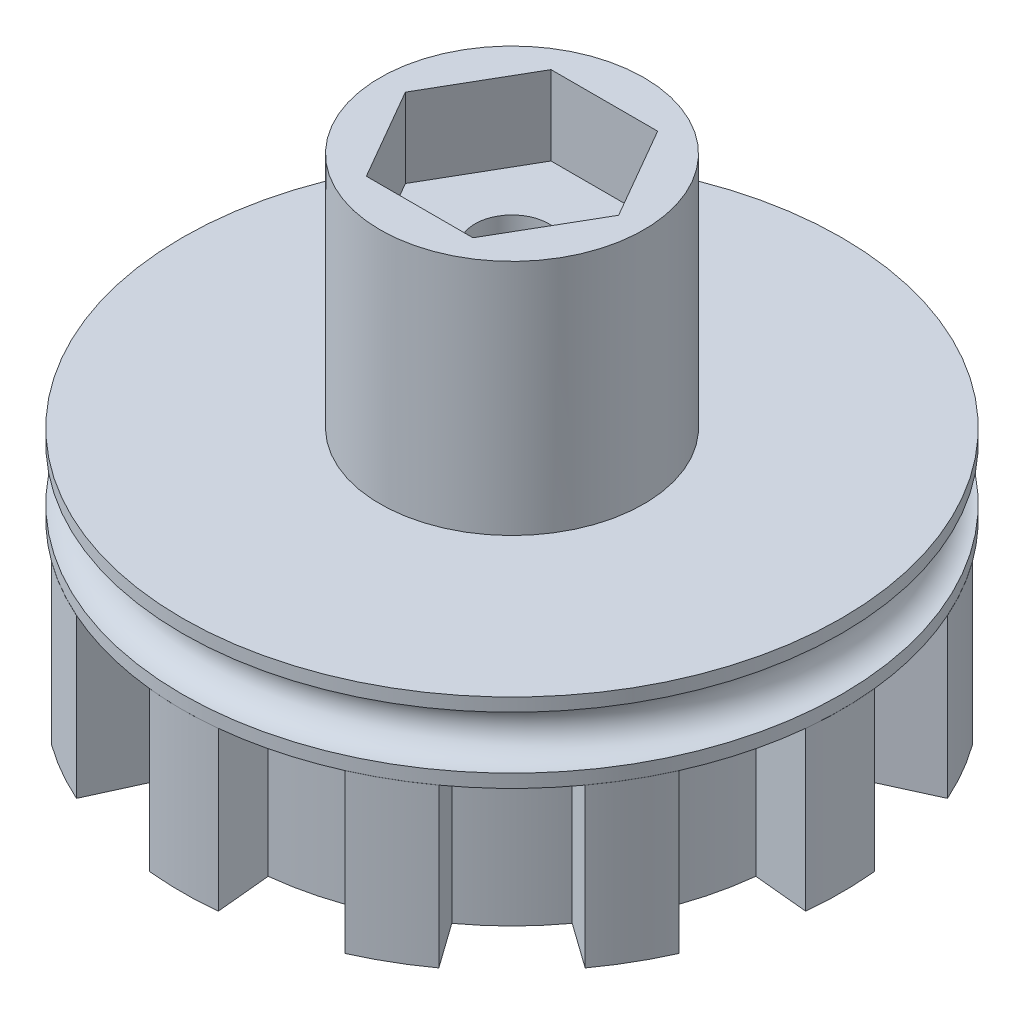
SolidWorks part; units mm, degrees
ref_plane "前视基准面" through (0, 0, 0) normal (0, 0, 1) x (1, 0, 0)
ref_plane "上视基准面" through (0, 0, 0) normal (0, 1, 0) x (1, 0, 0)
ref_plane "右视基准面" through (0, 0, 0) normal (1, 0, 0) x (0, 0, -1)
sketch "草图2" plane through (0, 0, 0) normal (0, 1, 0) x (1, 0, 0)
  line L0 (0, 13.0353) -> (0, -8.9877) construction
  line L1 (-1.1, 10.3417) -> (-1.3, 12.4322)
  line L2 (1.1, 10.3417) -> (1.3, 12.4322)
  line L3 (4.2182, 9.5061) -> (5.0903, 11.4166)
  line L4 (6.1235, 8.4061) -> (7.3419, 10.1166)
  line L5 (8.4061, 6.1235) -> (10.1166, 7.3419)
  line L6 (9.5061, 4.2182) -> (11.4166, 5.0903)
  line L7 (10.3417, 1.1) -> (12.4322, 1.3)
  line L8 (10.3417, -1.1) -> (12.4322, -1.3)
  line L9 (9.5061, -4.2182) -> (11.4166, -5.0903)
  line L10 (8.4061, -6.1235) -> (10.1166, -7.3419)
  line L11 (6.1235, -8.4061) -> (7.3419, -10.1166)
  line L12 (4.2182, -9.5061) -> (5.0903, -11.4166)
  line L13 (1.1, -10.3417) -> (1.3, -12.4322)
  line L14 (-1.1, -10.3417) -> (-1.3, -12.4322)
  line L15 (-4.2182, -9.5061) -> (-5.0903, -11.4166)
  line L16 (-6.1235, -8.4061) -> (-7.3419, -10.1166)
  line L17 (-8.4061, -6.1235) -> (-10.1166, -7.3419)
  line L18 (-9.5061, -4.2182) -> (-11.4166, -5.0903)
  line L19 (-10.3417, -1.1) -> (-12.4322, -1.3)
  line L20 (-10.3417, 1.1) -> (-12.4322, 1.3)
  line L21 (-9.5061, 4.2182) -> (-11.4166, 5.0903)
  line L22 (-8.4061, 6.1235) -> (-10.1166, 7.3419)
  line L23 (-6.1235, 8.4061) -> (-7.3419, 10.1166)
  line L24 (-4.2182, 9.5061) -> (-5.0903, 11.4166)
  arc A0 (-1.1, 10.3417) -> (-4.2182, 9.5061) centre (0, 0) ccw
  arc A1 (1.3, 12.4322) -> (-1.3, 12.4322) centre (0, 0) ccw
  arc A2 (7.3419, 10.1166) -> (5.0903, 11.4166) centre (0, 0) ccw
  arc A3 (11.4166, 5.0903) -> (10.1166, 7.3419) centre (0, 0) ccw
  arc A4 (12.4322, -1.3) -> (12.4322, 1.3) centre (0, 0) ccw
  arc A5 (10.1166, -7.3419) -> (11.4166, -5.0903) centre (0, 0) ccw
  arc A6 (5.0903, -11.4166) -> (7.3419, -10.1166) centre (0, 0) ccw
  arc A7 (-1.3, -12.4322) -> (1.3, -12.4322) centre (0, 0) ccw
  arc A8 (-7.3419, -10.1166) -> (-5.0903, -11.4166) centre (0, 0) ccw
  arc A9 (-11.4166, -5.0903) -> (-10.1166, -7.3419) centre (0, 0) ccw
  arc A10 (-12.4322, 1.3) -> (-12.4322, -1.3) centre (0, 0) ccw
  arc A11 (-10.1166, 7.3419) -> (-11.4166, 5.0903) centre (0, 0) ccw
  arc A12 (-5.0903, 11.4166) -> (-7.3419, 10.1166) centre (0, 0) ccw
  arc A13 (-6.1235, 8.4061) -> (-8.4061, 6.1235) centre (0, 0) ccw
  arc A14 (-9.5061, 4.2182) -> (-10.3417, 1.1) centre (0, 0) ccw
  arc A15 (-10.3417, -1.1) -> (-9.5061, -4.2182) centre (0, 0) ccw
  arc A16 (-8.4061, -6.1235) -> (-6.1235, -8.4061) centre (0, 0) ccw
  arc A17 (-4.2182, -9.5061) -> (-1.1, -10.3417) centre (0, 0) ccw
  arc A18 (1.1, -10.3417) -> (4.2182, -9.5061) centre (0, 0) ccw
  arc A19 (6.1235, -8.4061) -> (8.4061, -6.1235) centre (0, 0) ccw
  arc A20 (9.5061, -4.2182) -> (10.3417, -1.1) centre (0, 0) ccw
  arc A21 (10.3417, 1.1) -> (9.5061, 4.2182) centre (0, 0) ccw
  arc A22 (8.4061, 6.1235) -> (6.1235, 8.4061) centre (0, 0) ccw
  arc A23 (4.2182, 9.5061) -> (1.1, 10.3417) centre (0, 0) ccw
  point P6 (-1.1034, 10.3776)
  point P56 (0, 0)
  dimension "D1" = 20.8
  dimension "D2" = 25
  dimension "D3" = 2.2
  dimension "D5" = 1.1
  dimension "D6" = 1.3
  dimension "D7" = 1.3
  dimension "D4" = 12
extrude "凸台-拉伸1" add sketch "草图2" along normal blind 6
sketch "草图3" plane through (0, 6, 0) normal (0, 1, 0) x (1, 0, 0)
  circle A0 centre (0, 0) radius 1.4
extrude "切除-拉伸1" cut sketch "草图3" against normal blind 6
sketch "草图4" plane through (0, 6, 0) normal (0, 1, 0) x (1, 0, 0)
  circle A0 centre (0, 0) radius 5
extrude "凸台-拉伸2" add sketch "草图4" along normal blind 12
sketch "草图5" plane through (0, 18, 0) normal (0, 1, 0) x (1, 0, 0)
  line L0 (-1, -1.118) -> (1, -1.118)
  arc A0 (1, -1.118) -> (-1, -1.118) centre (0, 0) ccw
  dimension "D1" = 3
  dimension "D2" = 2
extrude "切除-拉伸2" cut sketch "草图5" against normal blind 12
sketch "草图6" plane through (0, 18, 0) normal (0, 1, 0) x (1, 0, 0)
  circle A0 centre (0, 0) radius 1.5
extrude "切除-拉伸3" cut sketch "草图6" against normal blind 31
sketch "草图7" plane through (0, 18, 0) normal (0, 1, 0) x (1, 0, 0)
  circle A0 centre (0, 0) radius 1.4
  circle A1 centre (0, 0) radius 1.5
extrude "凸台-拉伸3" add sketch "草图7" against normal blind 18
sketch "草图8" plane through (0, 18, 0) normal (0, 1, 0) x (1, 0, 0)
  line L1 (4.0415, 0) -> (2.0207, 3.5)
  line L2 (2.0207, 3.5) -> (-2.0207, 3.5)
  line L3 (-2.0207, 3.5) -> (-4.0415, 0)
  line L4 (-4.0415, 0) -> (-2.0207, -3.5)
  line L5 (-2.0207, -3.5) -> (2.0207, -3.5)
  line L6 (2.0207, -3.5) -> (4.0415, 0)
  circle A0 centre (0, 0) radius 3.5 construction
  dimension "D1" = 7
extrude "切除-拉伸4" cut sketch "草图8" against normal blind 3
sketch "草图9" plane through (0, 0, 0) normal (1, 0, 0) x (0, 0, -1)
  line L0 (0, 17.6689) -> (0, -1.8122) construction
  line L1 (4.2182, 6) -> (5.0903, 6) construction
  line L2 (5, 6) -> (12.4962, 6)
  line L3 (5, 6) -> (5, 9)
  line L4 (5, 9) -> (12.4962, 9)
  line L5 (12.4962, 6) -> (12.4962, 6.5)
  line L6 (5, 6) -> (5, 18) construction
  line L7 (12.4962, 8.5) -> (12.4962, 9)
  arc A0 (12.4962, 8.5) -> (12.4962, 6.5) centre (12.4962, 7.5) ccw
  dimension "D1" = 3
revolve "旋转1" add sketch "草图9" angle 360 about L0
